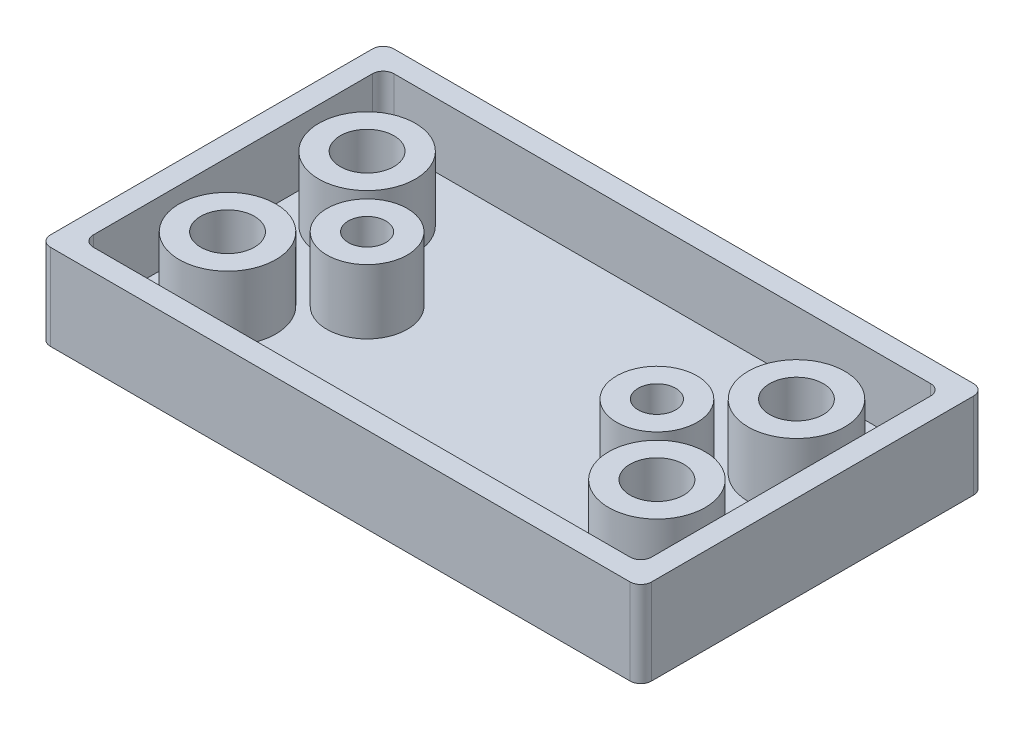
SolidWorks part; units mm, degrees
ref_plane "Front Plane" through (0, 0, 0) normal (0, 0, 1) x (1, 0, 0)
ref_plane "Top Plane" through (0, 0, 0) normal (0, 1, 0) x (1, 0, 0)
ref_plane "Right Plane" through (0, 0, 0) normal (1, 0, 0) x (0, 0, -1)
sketch "Sketch1" plane through (0, 0, 0) normal (0, 1, 0) x (1, 0, 0)
  line L0 (-28, -16) -> (-28, 16)
  line L1 (-26, -14) -> (26, -14)
  line L2 (-26, -14) -> (-26, 14)
  line L3 (-26, 14) -> (26, 14)
  line L4 (26, -14) -> (26, 14)
  line L5 (-26, -14) -> (26, 14) construction
  line L6 (-26, 14) -> (26, -14) construction
  line L7 (-28, 16) -> (28, 16)
  line L8 (28, -16) -> (28, 16)
  line L9 (-28, -16) -> (28, -16)
  point P0 (0, 0)
  dimension "D1" = 52
  dimension "D2" = 28
  dimension "D3" = 2
extrude "Boss-Extrude1" add sketch "Sketch1" along normal blind 8
sketch "Sketch2" plane through (0, 0, 0) normal (0, 1, 0) x (1, 0, 0)
  line L4 (-28, -16) -> (28, -16)
  line L5 (28, -16) -> (28, 16)
  line L6 (28, 16) -> (-28, 16)
  line L7 (-28, 16) -> (-28, -16)
  line L8 (-28, -16) -> (28, -16)
  line L9 (28, -16) -> (28, 16)
  line L10 (28, 16) -> (-28, 16)
  line L11 (-28, 16) -> (-28, -16)
  dimension "D1" = 0
extrude "Boss-Extrude2" add sketch "Sketch2" along normal blind 2
sketch "Sketch3" plane through (0, 2, 0) normal (0, 1, 0) x (1, 0, 0)
  circle A0 centre (13.5, 0) radius 1.75
  circle A1 centre (13.5, 0) radius 3.75
  circle A2 centre (20, 6.5) radius 2.5
  circle A3 centre (20, 6.5) radius 4.5
  dimension "D1" = 3.5
  dimension "D4" = 5
  dimension "D3" = 13.5
  dimension "D6" = 20
  dimension "D7" = 6.5
  dimension "D2" = 2
  dimension "D5" = 2
extrude "Boss-Extrude3" add sketch "Sketch3" along normal blind 6
mirror "Mirror1" about plane through (0, 0, 0) normal (0, 0, 1) of "Boss-Extrude3"
mirror "Mirror2" about plane through (0, 0, 0) normal (1, 0, 0) of "Mirror1", "Boss-Extrude3"
fillet "Fillet1" radius 1 8 edges at (-28, 4, -16) (-26, 5, -14) (28, 4, -16) (26, 5, -14) (26, 5, 14) (28, 4, 16) (-26, 5, 14) (-28, 4, 16)
